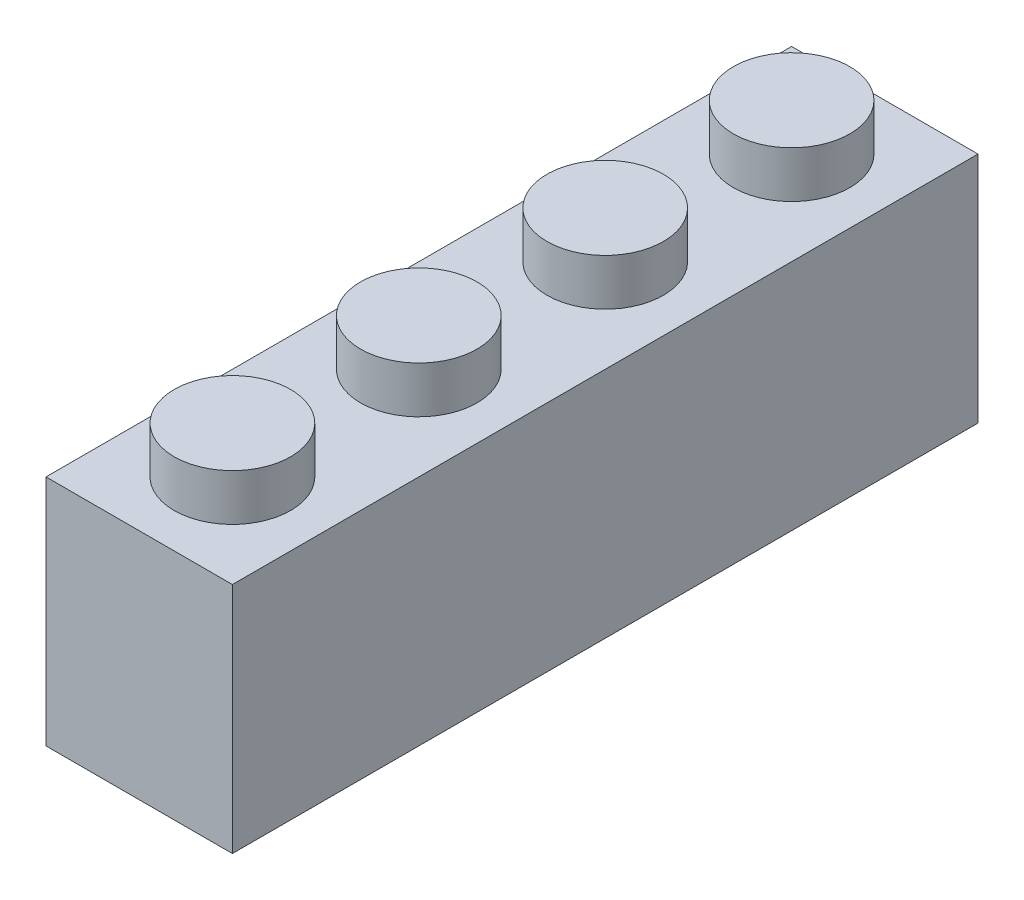
SolidWorks part; units mm, degrees
ref_plane "Front" through (0, 0, 0) normal (0, 0, 1) x (1, 0, 0)
ref_plane "Top" through (0, 0, 0) normal (0, 1, 0) x (1, 0, 0)
ref_plane "Right" through (0, 0, 0) normal (1, 0, 0) x (0, 0, -1)
other "Configuration Table"
other "PropertyManager"
sketch "Sketch1" plane through (0, 0, 0) normal (0, 1, 0) x (1, 0, 0)
  line L0 (-4, 16) -> (4, -16) construction
  line L1 (-4, 16) -> (4, 16)
  line L2 (-4, 16) -> (-4, -16)
  line L3 (-4, -16) -> (4, -16)
  line L4 (4, 16) -> (4, -16)
  dimension "length" = 32
  dimension "width" = 8
extrude "Base-Extrude" add sketch "Sketch1" along normal mid plane 10
sketch "Sketch2" plane through (0, 5, 0) normal (0, 1, 0) x (-1, 0, 0)
  line L0 (4, 16) -> (-4, 16) construction
  line L1 (-4, 16) -> (-4, -16) construction
  circle A0 centre (0, 12) radius 2.5
  dimension "D1" = 5
  dimension "D2" = 4
  dimension "D3" = 4
extrude "Boss-Extrude1" add sketch "Sketch2" along normal blind 2
pattern_linear "Top Button Pattern" count 4 spacing 8 along (0, 0, -1) of "Boss-Extrude1"
shell "Shell1" thickness 1
sketch "Sketch3" plane through (0, 4, 0) normal (0, -1, 0) x (1, 0, 0)
  line L0 (4, 16) -> (4, -16) construction
  line L4 (-4, 16) -> (4, 16) construction
  circle A0 centre (0, 8) radius 1
  dimension "D2" = 8
  dimension "thindiam" = 2
  dimension "D1" = 4
extrude "Bottom Post" add sketch "Sketch3" along normal offset from surface (8 mm away) 1 up to face at (0, -5, 0)
pattern_linear "Bottom Post Pattern" count 3 spacing 8 along (0, 0, -1) of "Bottom Post"
sketch "Sketch4" plane through (0, 4, 0) normal (0, -1, 0) x (1, 0, 0)
  line L0 (4, 16) -> (4, -16) construction
  line L2 (4, -16) -> (-4, -16) construction
  circle A0 centre (-4, -8) radius 2.5
  dimension "D1" = 8
  dimension "D2" = 8
  dimension "D3" = 5
extrude "Bottom ring" [suppressed] add sketch "Sketch4" along normal offset from surface (7 mm away) 2 thin
pattern_linear "Bottom Ring Pattern" [suppressed] count 2 spacing 8
equation "\"height\" = 4"
equation "\"width\"= 1"
equation "\"length@Sketch1\"=8*\"height\""
equation "\"width@Sketch1\"=8*\"width\""
equation "\"D1@Top Button Pattern\"=\"height\""
equation "\"D2@Top Button Pattern\"=\"width\""
